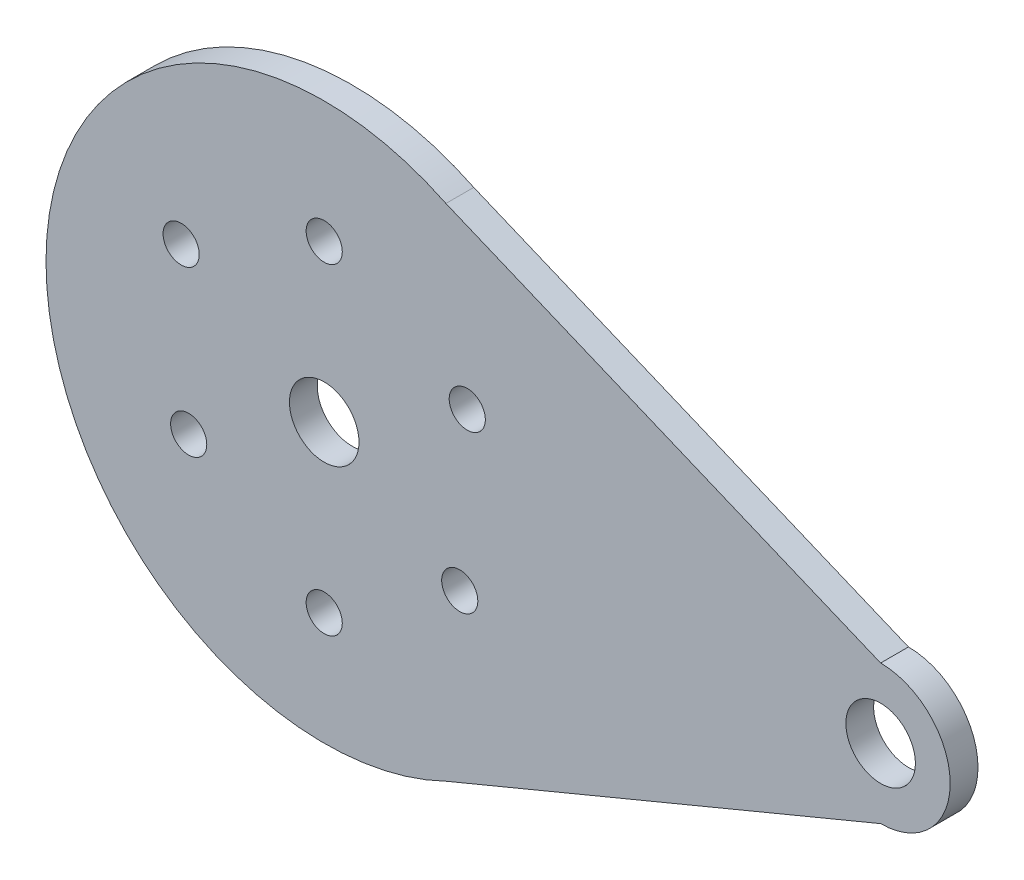
SolidWorks part; units mm, degrees
ref_plane "前视基准面" through (0, 0, 0) normal (0, 0, 1) x (1, 0, 0)
ref_plane "上视基准面" through (0, 0, 0) normal (0, 1, 0) x (1, 0, 0)
ref_plane "右视基准面" through (0, 0, 0) normal (1, 0, 0) x (0, 0, -1)
sketch "草图2" plane through (0, 0, 0) normal (0, 0, 1) x (1, 0, 0)
  line L0 (0.3866, -1.0315) -> (39.659, -23.7054) construction
  line L1 (0.3866, -1.0315) -> (80.3866, -1.0315) construction
  line L2 (17.8866, 34.9372) -> (80.3866, 8.9685)
  line L3 (17.8866, -37.0002) -> (80.3866, -11.0315)
  circle A0 centre (0.3866, -1.0315) radius 23.75 construction
  circle A1 centre (0.3866, -1.0315) radius 22.5 construction
  circle A2 centre (0.3866, -24.7815) radius 2.6
  circle A3 centre (19.8721, -12.2815) radius 2.6
  circle A4 centre (0.3866, -1.0315) radius 40 construction
  arc A5 (17.8866, 34.9372) -> (17.8866, -37.0002) centre (0.3866, -1.0315) ccw
  circle A6 centre (0.3866, -1.0315) radius 5
  circle A7 centre (-20.1815, 10.8435) radius 2.6
  circle A8 centre (20.9547, 10.8435) radius 2.6
  circle A9 centre (-19.099, -12.2815) radius 2.6
  circle A10 centre (0.3866, 21.4685) radius 2.6
  circle A11 centre (80.3866, -1.0315) radius 5
  circle A12 centre (80.3866, -1.0315) radius 10 construction
  arc A13 (80.3866, 8.9685) -> (80.3866, -11.0315) centre (80.3866, -1.0315) cw
  dimension "D1" = 45
  dimension "D2" = 5.2
  dimension "D3" = 5.2
  dimension "D4" = 80
  dimension "D5" = 10
extrude "凸台-拉伸1" add sketch "草图2" along normal blind 4
